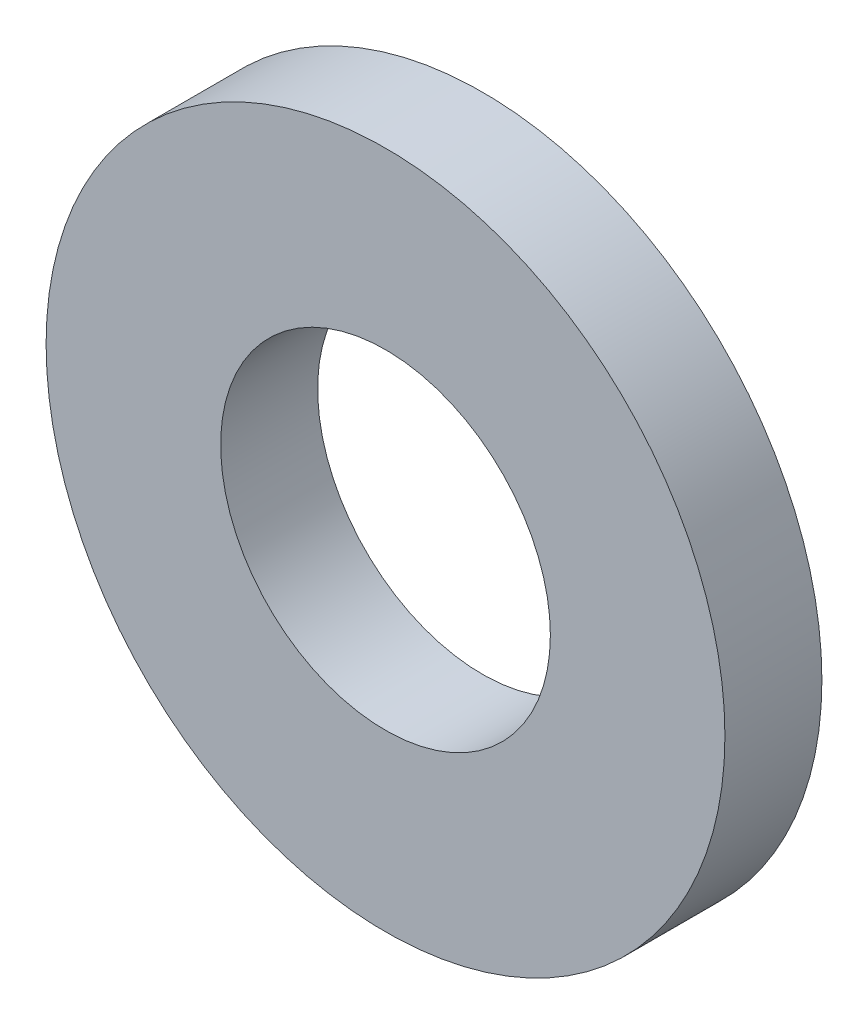
SolidWorks part; units mm, degrees
ref_plane "前视基准面" through (0, 0, 0) normal (0, 0, 1) x (1, 0, 0)
ref_plane "上视基准面" through (0, 0, 0) normal (0, 1, 0) x (1, 0, 0)
ref_plane "右视基准面" through (0, 0, 0) normal (1, 0, 0) x (0, 0, -1)
sketch "草图1" plane through (0, 0, 0) normal (0, 0, 1) x (1, 0, 0)
  circle A0 centre (0, 0) radius 3.5
  dimension "D1" = 7
extrude "金属件无牙型包络" add sketch "草图1" along normal blind 1
sketch "草图2" plane through (0, 0, 0) normal (0, 0, 1) x (1, 0, 0)
  circle A0 centre (0, 0) radius 1.7
  dimension "D1" = 3.4
extrude "内孔_装配间隙" cut sketch "草图2" along normal blind 1
